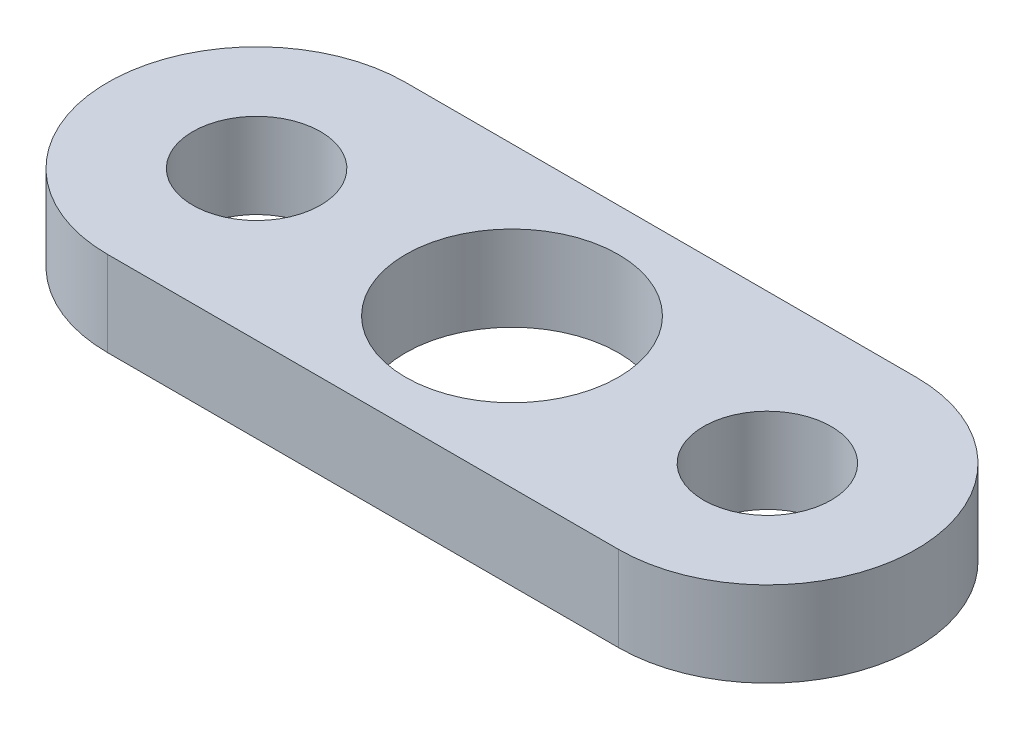
SolidWorks part; units mm, degrees
material "201.0-T43 Odlew izolowanej formy (SS)"
ref_plane "Płaszczyzna przednia" through (0, 0, 0) normal (0, 0, 1) x (1, 0, 0)
ref_plane "Płaszczyzna górna" through (0, 0, 0) normal (0, 1, 0) x (1, 0, 0)
ref_plane "Płaszczyzna prawa" through (0, 0, 0) normal (1, 0, 0) x (0, 0, -1)
sketch "Szkic1" plane through (0, 0, 0) normal (0, 1, 0) x (1, 0, 0)
  line L0 (0, 0) -> (6, 0) construction
  line L1 (0, -55) -> (0, 55) construction
  line L2 (-6, 0) -> (6, 0) construction
  line L3 (-6, 3.5) -> (6, 3.5)
  line L4 (-6, -3.5) -> (6, -3.5)
  circle A0 centre (6, 0) radius 1.5
  circle A1 centre (-6, 0) radius 1.5
  arc A2 (-6, 3.5) -> (-6, -3.5) centre (-6, 0) ccw
  arc A3 (6, -3.5) -> (6, 3.5) centre (6, 0) ccw
  circle A4 centre (0, 0) radius 2.5
  point P8 (0, 0)
  dimension "D2" = 3
  dimension "D3" = 2
  dimension "D4" = 5
  dimension "D1" = 6
extrude "Dodanie-wyciągnięcie1" add sketch "Szkic1" along normal blind 2
